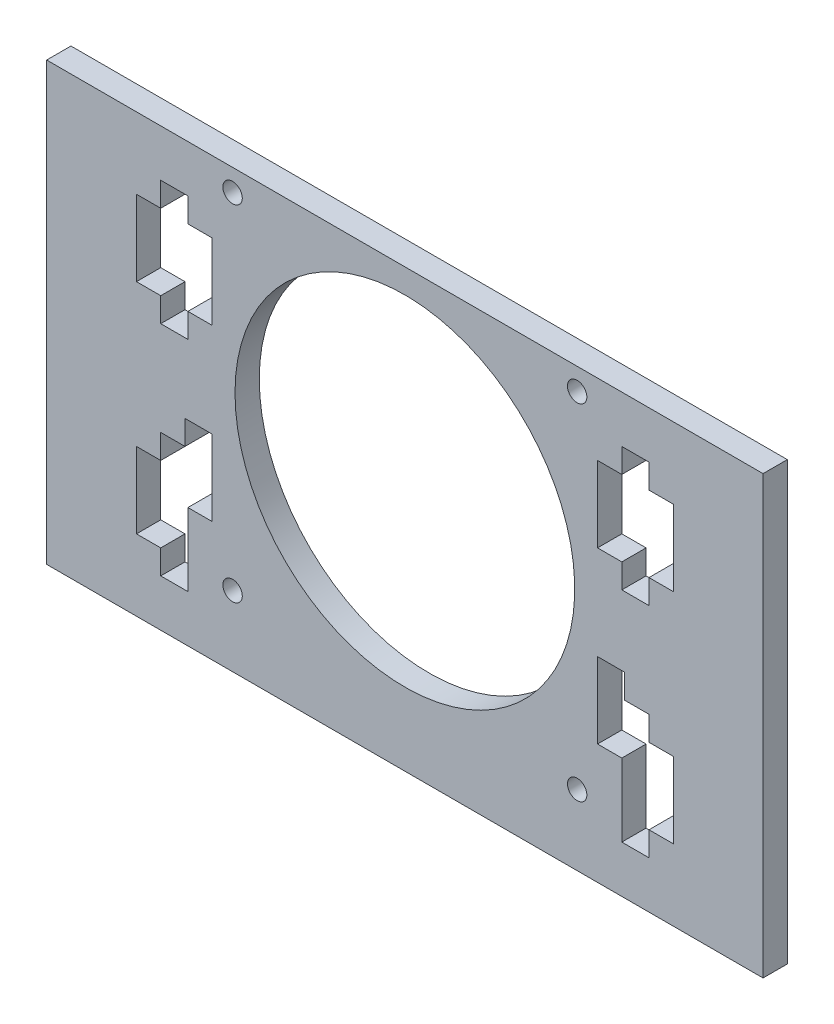
SolidWorks part; units mm, degrees
ref_plane "Спереди" through (0, 0, 0) normal (0, 0, 1) x (1, 0, 0)
ref_plane "Сверху" through (0, 0, 0) normal (0, 1, 0) x (1, 0, 0)
ref_plane "Справа" through (0, 0, 0) normal (1, 0, 0) x (0, 0, -1)
sketch "Sketch2" plane through (0, 0, 0) normal (0, 0, -1) x (-1, 0, 0)
  line L0 (-30.7767, 14.267) -> (-25.7767, 14.267)
  line L3 (-144.2767, 28.967) -> (-144.2767, -46.033)
  line L24 (-25.7767, 14.267) -> (-25.7767, 19.267)
  line L25 (-20.1767, 19.267) -> (-25.7767, 19.267)
  line L26 (3.3233, 28.967) -> (3.3233, -46.033)
  line L139 (3.3233, 28.967) -> (-144.2767, 28.967)
  line L140 (-57.8209, -11.033) -> (-80.1169, -11.033) construction
  line L155 (3.3233, -46.033) -> (3.3233, -61.033)
  line L156 (3.3233, -61.033) -> (-144.2767, -61.033)
  line L157 (-144.2767, -61.033) -> (-144.2767, -46.033)
  line L158 (-20.1767, 14.267) -> (-20.1767, 19.267)
  line L159 (-15.1767, 14.267) -> (-20.1767, 14.267)
  line L160 (-15.1767, 14.267) -> (-15.1767, -1.333)
  line L161 (-15.1767, -1.333) -> (-20.1767, -1.333)
  line L162 (-20.1767, -6.333) -> (-20.1767, -1.333)
  line L163 (-20.1767, -6.333) -> (-25.7767, -6.333)
  line L164 (-25.7767, -6.333) -> (-25.7767, -1.333)
  line L165 (-30.7767, -1.333) -> (-25.7767, -1.333)
  line L166 (-30.7767, 14.267) -> (-30.7767, -1.333)
  line L167 (-115.1767, -6.333) -> (-115.1767, -1.333)
  line L168 (-110.1767, -1.333) -> (-115.1767, -1.333)
  line L169 (-110.1767, 14.267) -> (-110.1767, -1.333)
  line L170 (-110.1767, 14.267) -> (-115.1767, 14.267)
  line L171 (-115.1767, 14.267) -> (-115.1767, 19.267)
  line L172 (-120.7767, 19.267) -> (-115.1767, 19.267)
  line L173 (-120.7767, 14.267) -> (-120.7767, 19.267)
  line L174 (-125.7767, 14.267) -> (-120.7767, 14.267)
  line L175 (-125.7767, 14.267) -> (-125.7767, -1.333)
  line L176 (-125.7767, -1.333) -> (-120.7767, -1.333)
  line L177 (-120.7767, -6.333) -> (-120.7767, -1.333)
  line L178 (-120.7767, -6.333) -> (-115.1767, -6.333)
  line L179 (-120.7767, -25.733) -> (-115.7767, -25.733)
  line L180 (-115.7767, -20.733) -> (-115.7767, -25.733)
  line L181 (-110.1767, -20.733) -> (-115.7767, -20.733)
  line L182 (-110.1767, -36.333) -> (-110.1767, -20.733)
  line L183 (-110.1767, -36.333) -> (-115.1767, -36.333)
  line L184 (-115.1767, -36.333) -> (-115.1767, -51.333)
  line L185 (-120.7767, -51.333) -> (-115.1767, -51.333)
  line L186 (-120.7767, -46.333) -> (-120.7767, -51.333)
  line L187 (-125.7767, -46.333) -> (-120.7767, -46.333)
  line L188 (-125.7767, -30.733) -> (-125.7767, -46.333)
  line L189 (-125.7767, -30.733) -> (-120.7767, -30.733)
  line L190 (-120.7767, -25.733) -> (-120.7767, -30.733)
  line L191 (-25.7767, -36.333) -> (-25.7767, -51.333)
  line L192 (-20.1767, -51.333) -> (-25.7767, -51.333)
  line L193 (-20.1767, -46.333) -> (-20.1767, -51.333)
  line L194 (-15.1767, -46.333) -> (-20.1767, -46.333)
  line L195 (-15.1767, -30.733) -> (-15.1767, -46.333)
  line L196 (-15.1767, -30.733) -> (-20.1767, -30.733)
  line L197 (-20.1767, -25.733) -> (-20.1767, -30.733)
  line L198 (-20.1767, -25.733) -> (-25.1767, -25.733)
  line L199 (-25.1767, -20.733) -> (-25.1767, -25.733)
  line L200 (-30.7767, -20.733) -> (-25.1767, -20.733)
  line L201 (-30.7767, -36.333) -> (-30.7767, -20.733)
  line L202 (-30.7767, -36.333) -> (-25.7767, -36.333)
  circle A1 centre (-70.4767, -11.033) radius 35
  circle A2 centre (-34.9767, 24.467) radius 2
  circle A3 centre (-105.9767, 24.467) radius 2
  circle A4 centre (-105.9767, -46.533) radius 2
  circle A5 centre (-34.9767, -46.533) radius 2
  dimension "D11" = 70
extrude "Boss-Extrude1" add sketch "Sketch2" along normal blind 5
